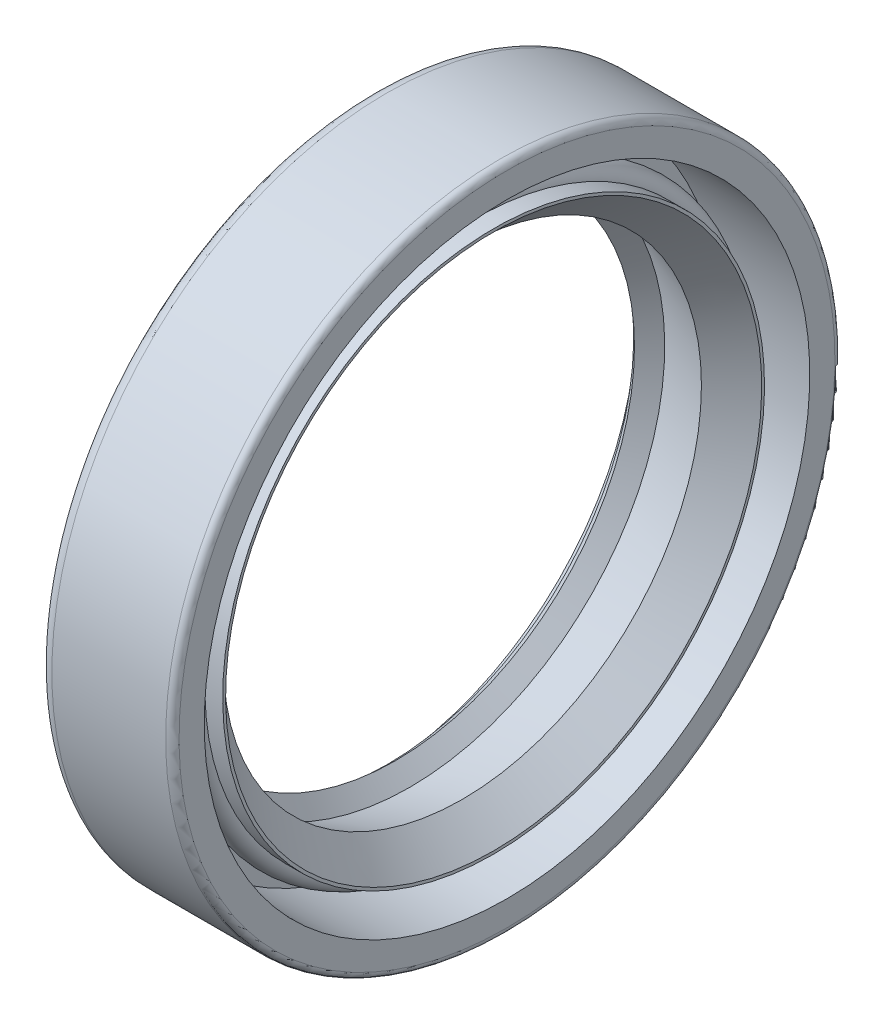
SolidWorks part; units mm, degrees
ref_plane "Front" through (0, 0, 0) normal (0, 0, 1) x (1, 0, 0)
ref_plane "Top" through (0, 0, 0) normal (0, 1, 0) x (1, 0, 0)
ref_plane "Right" through (0, 0, 0) normal (1, 0, 0) x (0, 0, -1)
sketch "Sketch1" plane through (0, 0, 0) normal (0, 0, 1) x (1, 0, 0)
  line L0 (0, 15.8333) -> (0.2188, 15.8333)
  line L1 (0.2188, 15.8333) -> (0.2188, 14.1667)
  line L2 (0.2188, 14.1667) -> (0, 14.1667)
  line L3 (0, 14.1667) -> (0, 13.75)
  line L4 (0, 13.75) -> (1.1667, 13.3333)
  line L5 (1.1667, 13.3333) -> (0.7525, 12.8712)
  line L6 (0.7525, 12.8712) -> (1.1667, 12.5)
  line L7 (1.1667, 12.5) -> (1.9136, 13.3333)
  line L8 (1.9136, 13.3333) -> (4.6667, 12.5)
  line L9 (4.6667, 12.5) -> (6.3, 14.0167)
  line L10 (6.3, 14.0167) -> (6.3, 14.1667)
  line L11 (6.3, 14.1667) -> (5.3667, 14.1667)
  line L12 (3.9667, 14.1667) -> (2.6833, 14.1667)
  line L13 (2.3333, 14.5167) -> (2.3333, 15.8333)
  line L14 (2.3333, 15.8333) -> (7, 15.8333)
  line L15 (7, 15.8333) -> (7, 17.15)
  line L16 (6.65, 17.5) -> (0.7, 17.5)
  line L17 (0, 16.8) -> (0, 15.8333)
  line L18 (7, 0) -> (0, 0) construction
  line L19 (1.1667, 12.5) -> (4.6667, 12.5) construction
  line L20 (3.675, 17.5) -> (3.675, 15.8333) construction
  line L21 (3.675, 15.8333) -> (3.675, 14.1667) construction
  line L22 (3.675, 14.1667) -> (3.675, 12.5) construction
  line L23 (4.6667, 14.1667) -> (4.6667, 12.5) construction
  line L24 (0, 16.3167) -> (2.3333, 16.3167) construction
  line L25 (2.3333, 16.3167) -> (4.6667, 16.3167) construction
  line L26 (4.6667, 16.3167) -> (7, 16.3167) construction
  line L27 (4.6667, 14.1667) -> (4.6667, 16.3167) construction
  line L28 (2.3333, 14.5167) -> (1.9136, 13.3333) construction
  line L29 (3.675, 13.3333) -> (1.9136, 13.3333) construction
  line L30 (2.7943, 13.3333) -> (2.7943, 14.1667) construction
  line L31 (2.7943, 13.75) -> (0, 13.75) construction
  line L32 (1.9136, 13.3333) -> (1.1667, 13.3333) construction
  line L33 (1.1667, 12.5) -> (1.1667, 13.3333) construction
  line L35 (7, 15.8333) -> (7, 14.1667) construction
  line L36 (7, 14.1667) -> (6.3, 14.1667) construction
  line L37 (0, 16.8) -> (0.7, 16.8) construction
  line L39 (1.1667, 16.3167) -> (1.1667, 13.3333) construction
  arc A0 (5.3667, 14.1667) -> (3.9667, 14.1667) centre (4.6667, 14.1667) ccw construction
  arc A1 (2.6833, 14.1667) -> (2.3333, 14.5167) centre (2.6833, 14.5167) cw
  arc A2 (7, 17.15) -> (6.65, 17.5) centre (6.65, 17.15) ccw
  arc A3 (0.7, 17.5) -> (0, 16.8) centre (0.7, 16.8) ccw
  arc A4 (3.9667, 14.1667) -> (5.3667, 14.1667) centre (4.6667, 14.1667) ccw
  dimension "D3" = 0.7
  dimension "D4" = 0.35
  dimension "D2" = 0.2188
  dimension "D5" = 67.784
  dimension "D8" = 47.121
revolve "Revolve1" add sketch "Sketch1" angle 360 about L18
sketch "Sketch2" plane through (0, 0, 0) normal (0, 0, 1) x (1, 0, 0)
  line L0 (0, 0) -> (7, 0) construction
  circle A0 centre (4.6667, 14.1667) radius 0.7
revolve "Revolve2" add sketch "Sketch2" angle 360 about L0
equation "\"D2@Sketch1\"=\"SealWidth@Sketch1\"*.03125"
equation "\"D3@Sketch1\"=\"SealWidth@Sketch1\"*.1"
equation "\"D4@Sketch1\"=\"D3@Sketch1\"*.5"
